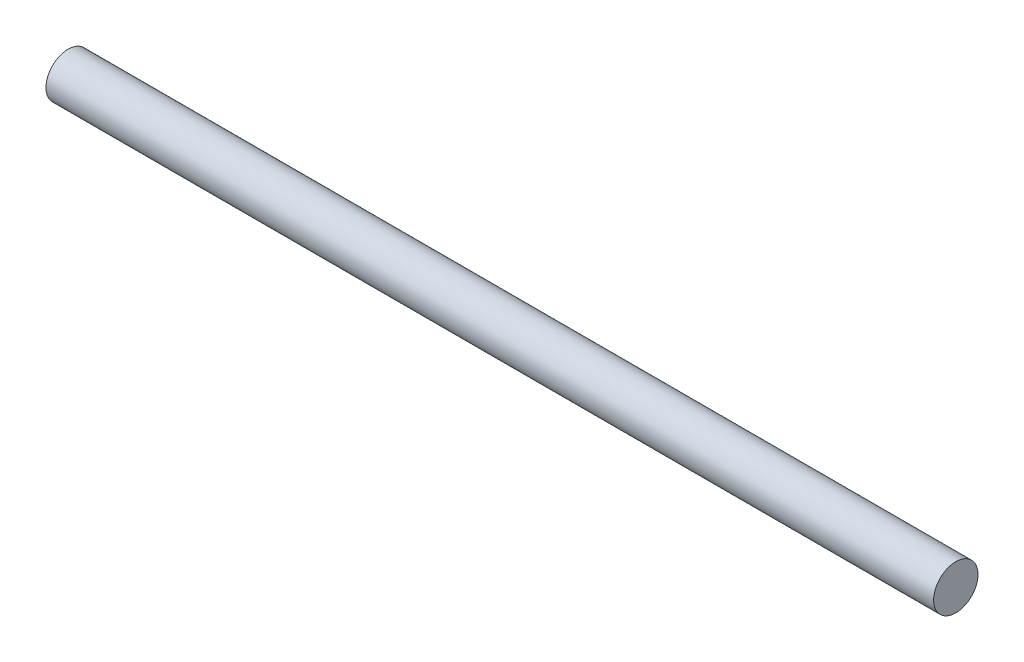
SolidWorks part; units mm, degrees
material "6061-T6 (SS)"
ref_plane "Front Plane" through (0, 0, 0) normal (0, 0, 1) x (1, 0, 0)
ref_plane "Top Plane" through (0, 0, 0) normal (0, 1, 0) x (1, 0, 0)
ref_plane "Right Plane" through (0, 0, 0) normal (1, 0, 0) x (0, 0, -1)
sketch "Sketch1" plane through (0, 0, 0) normal (1, 0, 0) x (0, 0, -1)
  circle A0 centre (0, 0) radius 12.7
  dimension "D1" = 25.4
extrude "Boss-Extrude1" add sketch "Sketch1" along normal blind 508
